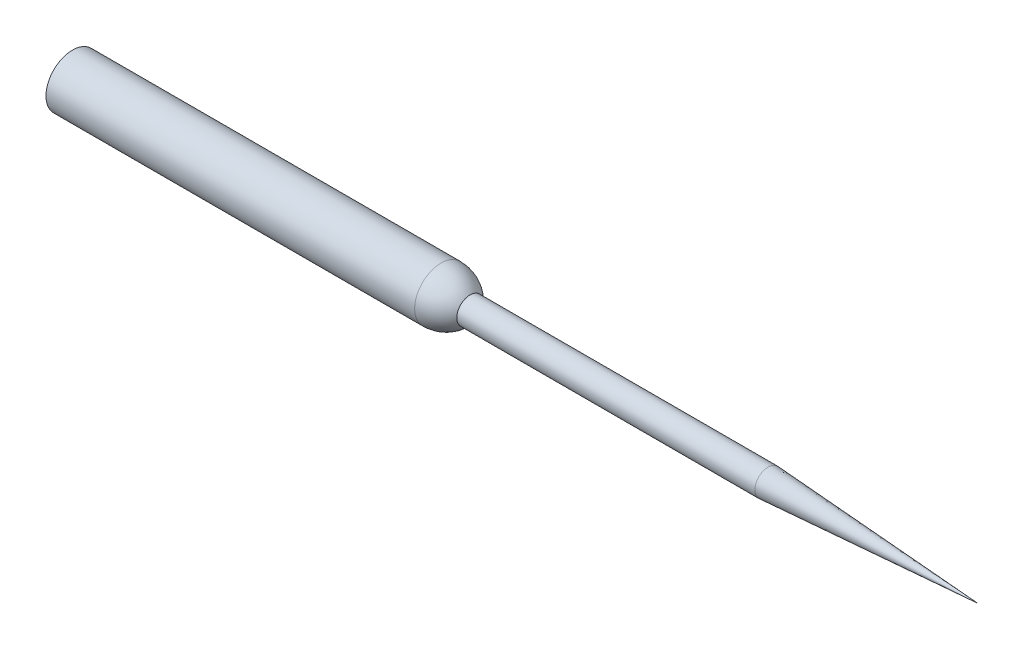
SolidWorks part; units mm, degrees
ref_plane "Front Plane" through (0, 0, 0) normal (0, 0, 1) x (1, 0, 0)
ref_plane "Top Plane" through (0, 0, 0) normal (0, 1, 0) x (1, 0, 0)
ref_plane "Right Plane" through (0, 0, 0) normal (1, 0, 0) x (0, 0, -1)
sketch "Sketch1" plane through (0, 0, 0) normal (0, 0, 1) x (1, 0, 0)
  line L1 (54.9077, 10.8151) -> (54.9077, 14.1429)
  line L2 (54.9077, 14.1429) -> (8.557, 14.1429)
  line L3 (8.557, 14.1429) -> (8.557, 10.8151)
  line L5 (96.029, 10.8151) -> (96.029, 12.479)
  line L7 (96.029, 12.479) -> (122.4132, 10.8151)
  line L9 (8.557, 10.8151) -> (122.4132, 10.8151)
  line L10 (58.5459, 12.479) -> (96.029, 12.479)
  line L11 (58.5459, 12.479) -> (96.029, 12.479)
  arc A1 (54.9077, 14.1429) -> (58.5459, 12.479) centre (54.9077, 9.3333) cw
revolve "Revolve4" add sketch "Sketch1" angle 360 about L9
scale "Scale1" scale about centroid uniform scaling yes scale factor 6
